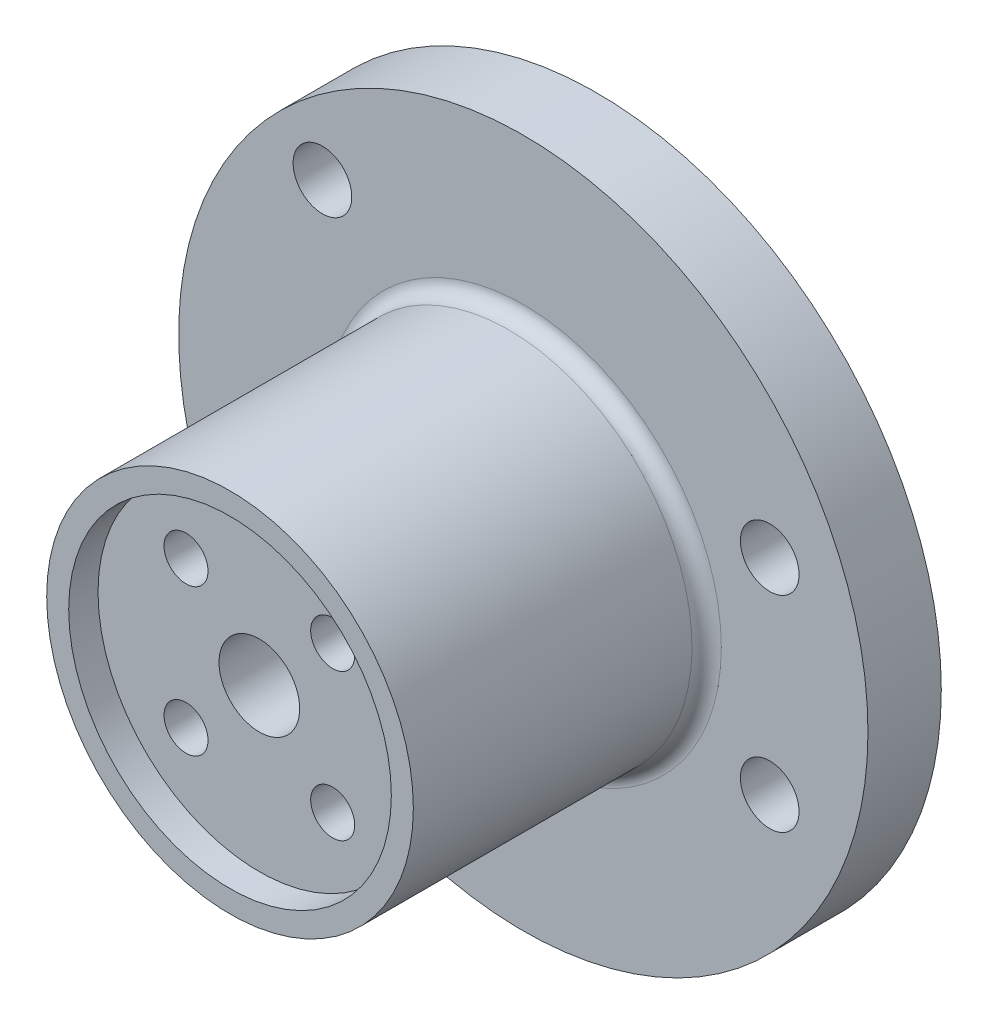
SolidWorks part; units mm, degrees
ref_plane "前视基准面" through (0, 0, 0) normal (0, 0, 1) x (1, 0, 0)
ref_plane "上视基准面" through (0, 0, 0) normal (0, 1, 0) x (1, 0, 0)
ref_plane "右视基准面" through (0, 0, 0) normal (1, 0, 0) x (0, 0, -1)
other "Configuration Table"
sketch "草图1" plane through (0, 0, 0) normal (0, 0, 1) x (1, 0, 0)
  line L0 (-1017.25, -29.8341) -> (48982.75, -29.8341) construction
  line L1 (-16.1993, -13.8341) -> (-16.1993, -45.8341) construction
  line L2 (0, -1000) -> (0, 49000) construction
  circle A0 centre (0, -29.8341) radius 23.5
  point P5 (-16.1993, -29.8341)
  dimension "D1" = 47
extrude "凸台-拉伸1" add sketch "草图1" along normal blind 5
sketch "草图2" plane through (0, 0, 0) normal (0, 0, -1) x (-1, 0, 0)
  circle A0 centre (13.6993, -15.8341) radius 2
  circle A1 centre (13.6993, -43.8341) radius 2
  circle A2 centre (-16.8007, -22.8841) radius 2
  circle A3 centre (-16.8007, -36.8841) radius 2
  circle A4 centre (13.6993, -29.8341) radius 2
extrude "切除-拉伸1" cut sketch "草图2" against normal through all
sketch "草图3" plane through (0, 0, 0) normal (0, 0, -1) x (-1, 0, 0)
  line L0 (-985.25, -29.8341) -> (49014.75, -29.8341) construction
  line L3 (0, -1000) -> (0, 49000) construction
  circle A0 centre (0, -29.8341) radius 12.5
  dimension "D1" = 25
extrude "凸台-拉伸3" add sketch "草图3" against normal blind 25
sketch "草图4" plane through (0, 0, 25) normal (0, 0, 1) x (1, 0, 0)
  line L1 (5, -34.8341) -> (-5, -34.8341)
  line L2 (5, -34.8341) -> (5, -24.8341)
  line L3 (5, -24.8341) -> (-5, -24.8341)
  line L4 (-5, -34.8341) -> (-5, -24.8341)
  line L5 (5, -34.8341) -> (-5, -24.8341) construction
  line L6 (5, -24.8341) -> (-5, -34.8341) construction
  circle A0 centre (0, -29.8341) radius 4
  circle A1 centre (-5, -34.8341) radius 1.5
  circle A2 centre (-5, -24.8341) radius 1.5
  circle A3 centre (5, -24.8341) radius 1.5
  circle A4 centre (5, -34.8341) radius 1.5
  dimension "D1" = 8
  dimension "D4" = 3
  dimension "D2" = 10
  dimension "D3" = 10
  dimension "D5" = 4
extrude "切除-拉伸2" cut sketch "草图4" against normal through all contours L3 A2 L4 | L4 A2 L3 | L2 A3 L3 | L3 A3 L2 | L1 A4 L2 | L2 A4 L1 | A0 | A1
sketch "草图5" plane through (0, 0, 25) normal (0, 0, 1) x (1, 0, 0)
  circle A0 centre (0, -29.8341) radius 11
  dimension "D1" = 22
extrude "切除-拉伸3" cut sketch "草图5" against normal blind 2
sketch "草图6" plane through (0, 0, 0) normal (0, 0, -1) x (-1, 0, 0)
  circle A0 centre (-5, -24.8341) radius 2.75
  circle A1 centre (0, -29.8341) radius 4
  circle A2 centre (0, -29.8341) radius 4
  circle A3 centre (5, -24.8341) radius 2.75
  circle A4 centre (0, -29.8341) radius 4
  circle A5 centre (5, -34.8341) radius 2.75
  circle A6 centre (0, -29.8341) radius 4
  circle A7 centre (-5, -34.8341) radius 2.75
  circle M1 centre (-5, -24.8341) radius 1.5
  circle M2 centre (-5, -34.8341) radius 1.5
  circle M3 centre (5, -34.8341) radius 1.5
  circle M5 centre (5, -24.8341) radius 1.5
  dimension "D1" = 5.5
  dimension "D2" = 4
extrude "切除-拉伸5" cut sketch "草图6" against normal blind 20 contours A0 M1 | A3 M5 | A7 M2 | A5 M3
sketch "草图7" plane through (0, 0, 0) normal (0, 0, -1) x (-1, 0, 0)
  circle A0 centre (0, -29.8341) radius 4
  circle A1 centre (0, -29.8341) radius 2.75
  dimension "D1" = 5.5
extrude "凸台-拉伸4" add sketch "草图7" against normal blind 23
fillet "圆角1" radius 1 1 edges at (12.5, -29.8341, 5)
